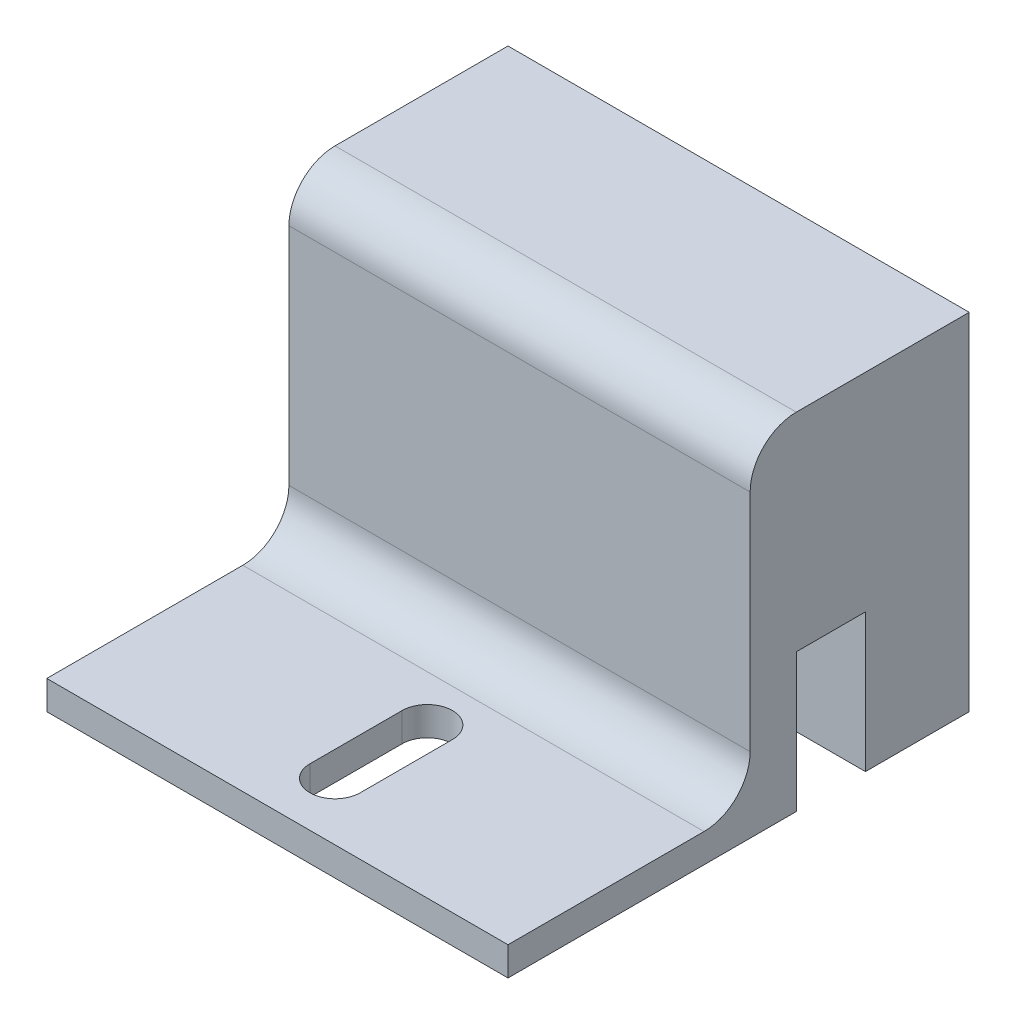
SolidWorks part; units mm, degrees
ref_plane "Front Plane" through (0, 0, 0) normal (0, 0, 1) x (1, 0, 0)
ref_plane "Top Plane" through (0, 0, 0) normal (0, 1, 0) x (1, 0, 0)
ref_plane "Right Plane" through (0, 0, 0) normal (1, 0, 0) x (0, 0, -1)
sketch "Sketch1" plane through (0, 0, 0) normal (1, 0, 0) x (0, 0, -1)
  line L0 (0, 0) -> (-11.43, 0)
  line L1 (-11.43, 0) -> (-11.43, 15.24)
  line L2 (-11.43, 15.24) -> (-19.05, 15.24)
  line L3 (-19.05, 15.24) -> (-19.05, 0)
  line L4 (-19.05, 0) -> (-50.8, 0)
  line L5 (-50.8, 0) -> (-50.8, 3.175)
  line L6 (-50.8, 3.175) -> (-24.13, 3.175)
  line L9 (-24.13, 3.175) -> (-24.13, 38.1)
  line L10 (-24.13, 38.1) -> (0, 38.1)
  line L11 (0, 38.1) -> (0, 0)
  point P3 (-24.9027, 4.2267)
  point P10 (0, 0)
  point P14 (-24.9027, 1.9275)
  point P15 (0, 0)
  dimension "D1" = 38.1
  dimension "D2" = 11.43
  dimension "D3" = 7.62
  dimension "D4" = 3.175
  dimension "D5" = 5.08
  dimension "D6" = 50.8
  dimension "D7" = 15.24
extrude "Boss-Extrude1" add sketch "Sketch1" along normal blind 50.8
sketch "Sketch2" plane through (0, 3.175, 0) normal (0, 1, 0) x (1, 0, 0)
  line L0 (25.4, -34.29) -> (25.4, -44.45) construction
  line L1 (28.1686, -34.29) -> (28.1686, -44.45)
  line L2 (22.6314, -34.29) -> (22.6314, -44.45)
  line L3 (50.8, -50.8) -> (0, -50.8) construction
  arc A0 (28.1686, -34.29) -> (22.6314, -34.29) centre (25.4, -34.29) ccw
  arc A1 (22.6314, -44.45) -> (28.1686, -44.45) centre (25.4, -44.45) ccw
  point P2 (25.4, -39.37)
  point P9 (0, 0)
  point P10 (25.4, -50.8)
  dimension "D1" = 5.5372
  dimension "D2" = 10.16
  dimension "D3" = 6.35
extrude "Cut-Extrude1" cut sketch "Sketch2" against normal through all
fillet "Fillet1" radius 5.08 2 edges at (25.4, 38.1, 24.13) (25.4, 3.175, 24.13)
